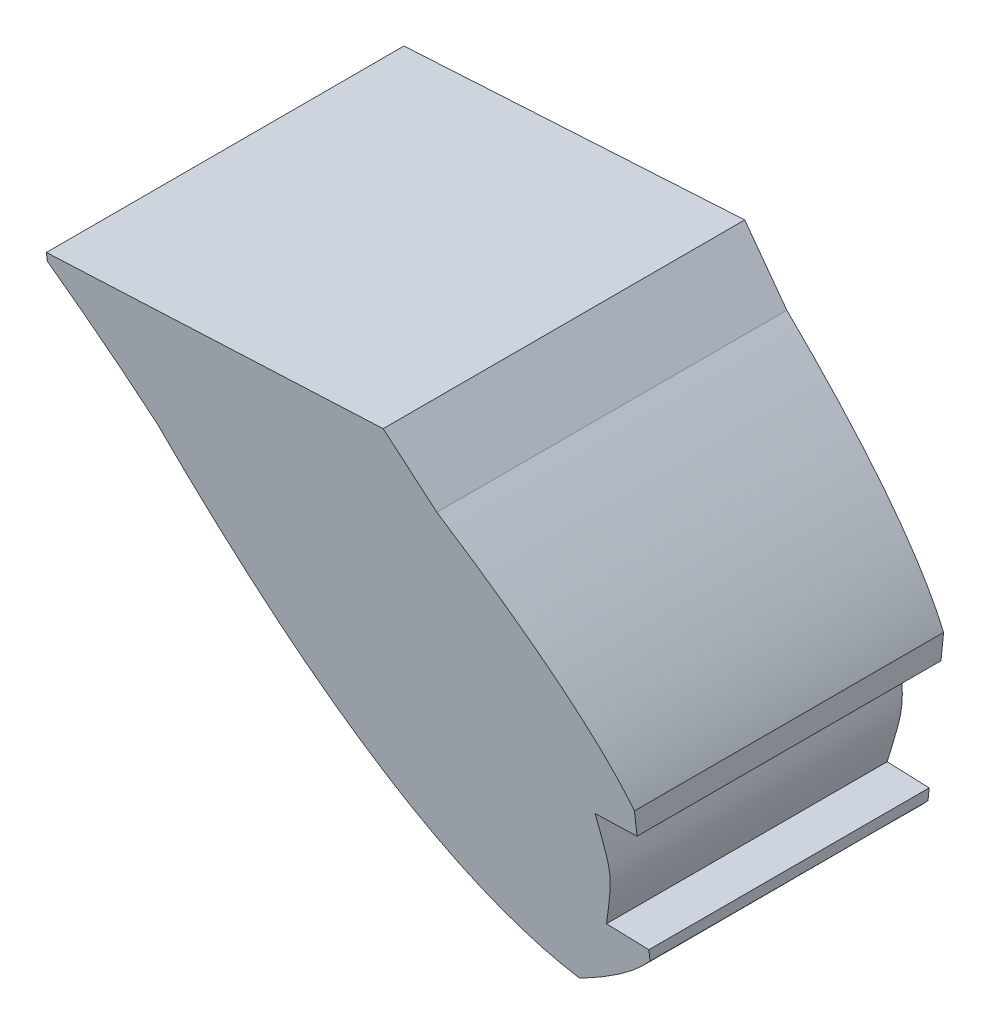
SolidWorks part; units mm, degrees
ref_plane "Alzado" through (0, 0, 0) normal (0, 0, 1) x (1, 0, 0)
ref_plane "Planta" through (0, 0, 0) normal (0, 1, 0) x (1, 0, 0)
ref_plane "Vista lateral" through (0, 0, 0) normal (1, 0, 0) x (0, 0, -1)
sketch "Croquis1" plane through (0, 0, 0) normal (0, 0, 1) x (1, 0, 0)
  line L0 (-8.9818, 12.6082) -> (-23.0359, 11.8716) construction
  line L1 (-8.9818, 12.6082) -> (-23.0359, 11.8716)
  line L2 (-8.9818, 12.6082) -> (-23.0359, 11.8716) construction
  line L4 (-8.9818, 12.6082) -> (-23.0359, 11.8716)
  line L6 (-1.3949, 1.9763) -> (0.3551, 2.2848) construction
  line L7 (-1.3949, 1.9763) -> (0.3551, 2.2848)
  line L8 (0.3551, 2.2848) -> (0.3551, 2.8423) construction
  line L9 (0.3551, 2.2848) -> (0.3551, 3.0015)
  line L10 (0.3551, -2.2848) -> (-1.3949, -2.2237) construction
  line L11 (0.3551, -2.2848) -> (-1.3949, -2.2237)
  line L12 (0.3551, 2.2848) -> (0.3551, -2.2848) construction
  line L13 (0.3551, -2.2848) -> (0.3551, -2.7233)
  line L14 (-8.9818, 12.6082) -> (-6.9949, 10.4774)
  line L15 (-23.0359, 11.5401) -> (-23.0359, 11.8716) construction
  line L16 (-23.0359, 11.5401) -> (-23.0359, 11.8716)
  arc A0 (-18.9452, 7.5409) -> (-23.0359, 11.5401) centre (-69.8841, -40.4718) ccw construction
  arc A1 (-18.9452, 7.5409) -> (-23.0359, 11.5401) centre (-69.8841, -40.4718) ccw
  spline S1 degree 2 poles (-1165.1036, 5893.6598) (818.9524, -5942.9252) (-471.5876, 5971.4584) knots 0.453698 0.453698 0.453698 0.546233 0.546233 0.546233 weights 1 1 1 only from (-18.9452, 7.5409) to (-2.8466, -5.0591) construction
  spline S2 degree 2 poles (-18.9452, 7.5409) (-10.215, -3.6976) (-2.8466, -5.0591) knots 0.497667 0.497667 0.497667 0.499554 0.499554 0.499554 weights 1 1 1
  spline S3 degree 2 poles (-5694.9897, 1886.3291) (5642.0208, -2053.6219) (-5584.6926, 2218.951) knots 0.453717 0.453717 0.453717 0.546322 0.546322 0.546322 weights 1 1 1 only from (0.3551, 3.0015) to (-6.9949, 10.4774) construction
  spline S4 degree 2 poles (0.3551, 3.0015) (-1.4487, 6.0584) (-6.9949, 10.4774) knots 0.500821 0.500821 0.500821 0.502013 0.502013 0.502013 weights 1 1 1
  spline S5 degree 2 poles (-1.3949, -2.2237) (-0.9075, -0.1237) (-1.3949, 1.9763) knots 0 0 0 1 1 1 weights 1 3.231801 1 construction
  spline S6 degree 2 poles (-1.3949, -2.2237) (-0.9075, -0.1237) (-1.3949, 1.9763) knots 0 0 0 1 1 1 weights 1 3.231801 1
  spline S7 degree 2 poles (-5992.358, 322.5754) (5976.1778, -523.0129) (-5953.8534, 722.2524) knots 0.453712 0.453712 0.453712 0.546274 0.546274 0.546274 weights 1 1 1 only from (-2.8466, -5.0591) to (0.3551, -2.7233) construction
  spline S8 degree 2 poles (-2.8466, -5.0591) (-0.7424, -3.9352) (0.3551, -2.7233) knots 0.498812 0.498812 0.498812 0.499413 0.499413 0.499413 weights 1 1 1
extrude "Saliente-Extruir1" add sketch "Croquis1" along normal mid plane 15 contours S2 S8 L13 L11 S6 L7 L9 S4 L14 L1 L16 A1
sketch "Croquis3" plane through (0, 0, 0) normal (0, 0, 1) x (1, 0, 0)
  line L0 (-6.742, 0) -> (0, 0) construction
  line L1 (-1.8181, 2) -> (-1.7771, 2.0103) construction
  line L3 (-1.8181, 2) -> (-0.1689, 2.4155) construction
  line L4 (-1.8181, 2) -> (0.3551, 3.0015)
  line L5 (0.3551, 3.0015) -> (0.3551, 0)
  line L6 (-1.9135, -2.1825) -> (0.3551, -2.2848)
  line L7 (0.3551, -2.2848) -> (0.3551, 0)
  parabola Q0 (-1.9135, -2.1825) -> (-1.8181, 2) focus (-3.3181, 0) apex (-1.3181, 0)
  dimension "D1" = 2
  dimension "D2" = 2
extrude "Cortar-Extruir1" [suppressed] cut sketch "Croquis3" against normal through all both and the other way through all
sketch "Croquis4" plane through (0, 0, 0) normal (0, 0, 1) x (1, 0, 0)
  line L0 (-1.3949, 1.9763) -> (0.3551, 2.2848) construction
  line L1 (-1.3949, 1.9763) -> (0.3551, 2.2848)
  line L2 (0.3551, 2.2848) -> (0.3551, 3.0015) construction
  line L3 (0.3551, 2.0374) -> (0.3551, 2.2848)
  line L4 (-1.3949, 1.9763) -> (0.3551, 2.0374)
  line L5 (0, 0) -> (-3.4665, 0) construction
  dimension "D1" = 2
extrude "Saliente-Extruir2" add sketch "Croquis4" along normal through all and the other way through all
sketch "Croquis7" plane through (0, 0, 0) normal (0, 0, 1) x (1, 0, 0)
  line L0 (0, 0) -> (-15.3945, 3.3171) construction
  line L1 (-17.3963, 18.9371) -> (-15.3945, 3.3171) construction
  line L2 (-15.3945, 3.3171) -> (-9.9316, -2.6296) construction
  line L3 (-15.3945, 3.3171) -> (-10.2385, 8.0535) construction
  line L4 (-17.3963, 18.9371) -> (-16.5429, 12.2783) construction
  line L5 (0, 0) -> (-1.3461, -2.2254) construction
  line L6 (-69.8841, 29.5282) -> (-81.9382, 42.5765) construction
  line L7 (-69.8841, 29.5282) -> (-20.9497, 29.5282) construction
  line L8 (-17.8101, 13.1658) -> (-25.5429, 13.1658)
  line L9 (-18.2059, 7.0951) -> (-21.9246, 11.9299) construction
  line L10 (0.3551, -2.5) -> (-2.4497, -2.0473)
  line L11 (-1.3461, -2.2254) -> (-2.0075, -3.6222) construction
  line L12 (-1.3461, -2.2254) -> (-1.4547, -2.8987) construction
  line L13 (-1.3461, -2.2254) -> (-1.2286, -1.4976) construction
  line L14 (0.3551, -2.2848) -> (0.3551, -2.7233) construction
  line L15 (0.3551, -2.2848) -> (-1.3949, -2.2237) construction
  line L16 (-2.0075, -3.6222) -> (-3.0629, -5.8512) construction
  line L17 (-2.6331, -4.9434) -> (-3.7044, -5.5324) construction
  line L18 (-2.6331, -4.9434) -> (-3.2248, -3.867) construction
  line L19 (-2.6331, -4.9434) -> (-2.2174, -6.1341) construction
  line L20 (-4.0838, -4.7637) -> (-1.6363, -5.0668) construction
  line L21 (-4.0838, -4.7637) -> (-0.036, -5.9454) construction
  line L22 (-4.0838, -4.7637) -> (-3.7621, -3.6616) construction
  line L23 (-4.0838, -4.7637) -> (-6.31, -3.7023) construction
  line L24 (-6.31, -3.7023) -> (-8.69, -2.5677) construction
  line L25 (-8.69, -2.5677) -> (-6.8421, -3.7725) construction
  line L26 (-8.69, -2.5677) -> (-7.9481, -1.4297) construction
  line L27 (-10.6884, -0.8477) -> (-8.69, -2.5677) construction
  line L28 (-10.6884, -0.8477) -> (-14.8546, 2.738) construction
  line L29 (-14.8546, 2.738) -> (-14.5337, 2.3989) construction
  line L30 (-14.8546, 2.738) -> (-14.6199, 2.9602) construction
  line L31 (-18.2059, 7.0951) -> (-14.8546, 2.738) construction
  line L32 (-8.9818, 12.6082) -> (-23.0359, 11.8716) construction
  line L33 (-8.9818, 12.6082) -> (-23.0359, 11.8716)
  line L34 (-21.9246, 11.9299) -> (-21.9826, 13.0367) construction
  line L35 (-21.9246, 11.9299) -> (-23.4156, 13.0367) construction
  arc A0 (-18.9452, 7.5409) -> (-23.0359, 11.5401) centre (-69.8841, -40.4718) ccw construction
  spline S0 degree 2 poles (-654.4568, 2937.5195) (409.3679, -2972.9237) (-163.476, 2987.5518) knots 0.467242 0.467242 0.467242 0.532662 0.532662 0.532662 weights 1 1 1 only from (-18.9452, 7.5409) to (-2.8466, -5.0591) construction
  spline S1 degree 2 poles (-18.6263, 7.1332) (-10.0803, -3.7225) (-2.8466, -5.0591) knots 0.497702 0.497702 0.497702 0.499554 0.499554 0.499554 weights 1 1 1 construction
  spline S3 degree 2 poles (-2999.4042, 119.7504) (2988.2948, -261.6206) (-2971.0465, 402.239) knots 0.467267 0.467267 0.467267 0.532713 0.532713 0.532713 weights 1 1 1 only from (-2.8466, -5.0591) to (0.3551, -2.7233) construction
  spline S4 degree 2 poles (-2.8466, -5.0591) (-2.7385, -5.0013) (-2.6331, -4.9434) knots 0.498812 0.498812 0.498812 0.498843 0.498843 0.498843 weights 1 1 1
  dimension "D1" = 2.5
  dimension "D2" = 22
  dimension "D3" = 16.17
  dimension "D4" = 54.138
  dimension "D5" = 34.566
  dimension "D6" = 50.413
sketch "Croquis6" plane through (0, 0, 0) normal (1, 0, 0) x (0, 0, -1)
  line L0 (7.5, 12.6082) -> (7.5, 10.4774) construction
  line L1 (7.5, 12.6082) -> (7.5, -5.0591)
  line L2 (-7.5, 12.6082) -> (-7.5, 10.4774) construction
  line L3 (-7.5, 12.6082) -> (-7.5, -5.0591)
  line L4 (-7.5, -5.0591) -> (7.5, -5.0591) construction
  line L5 (-7.5, -5.0591) -> (-5.5, -5.0591)
  line L6 (7.5, 12.6082) -> (5.5, -5.0591)
  line L7 (-7.5, 12.6082) -> (-5.5, -5.0591)
  line L8 (5.5, -5.0591) -> (7.5, -5.0591)
  dimension "D1" = 2
  dimension "D2" = 2
extrude "Cortar-Extruir2" cut sketch "Croquis6" against normal through all and the other way through all
